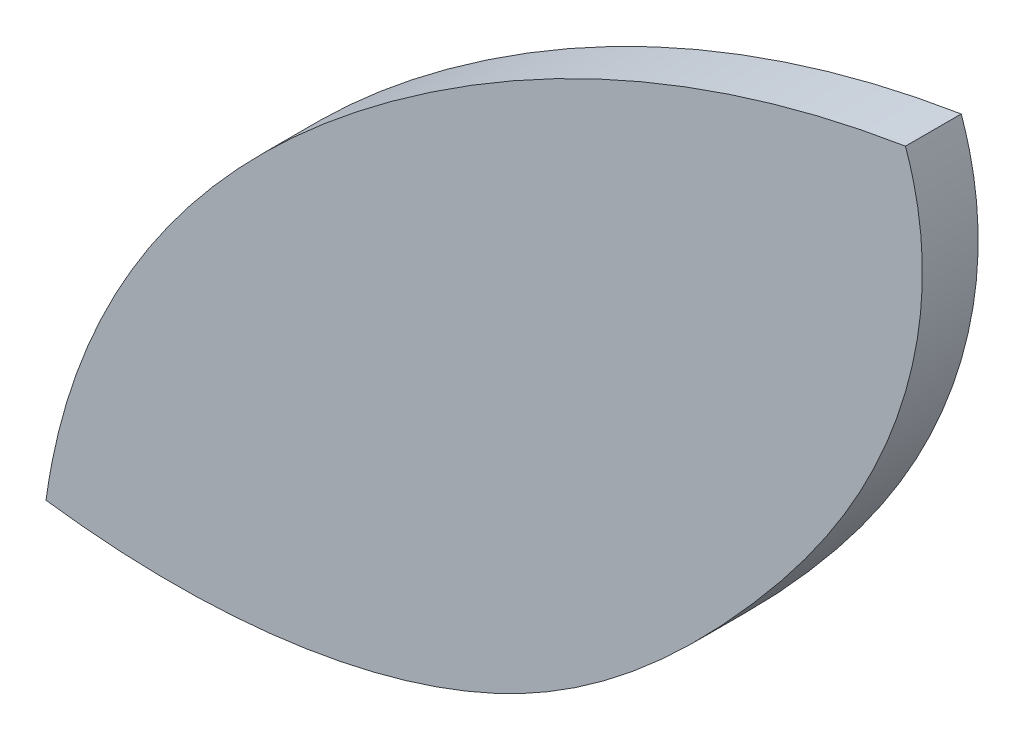
SolidWorks part; units mm, degrees
ref_plane "Piano frontale" through (0, 0, 0) normal (0, 0, 1) x (1, 0, 0)
ref_plane "Piano superiore" through (0, 0, 0) normal (0, 1, 0) x (1, 0, 0)
ref_plane "Piano destro" through (0, 0, 0) normal (1, 0, 0) x (0, 0, -1)
sketch "Schizzo1" plane through (0, 0, 0) normal (0, 0, 1) x (1, 0, 0)
  spline S0 degree 3 poles (0, 0) (1.6435, 12.058) (16.3251, 29.416) (36.5777, 38.0555) (46.2265, 39.6066) knots 0 0 0 0 0.544922 1 1 1 1
  spline S1 degree 3 poles (46.2265, 39.6066) (47.9349, 34.8478) (46.2539, 24.7967) (37.6438, 13.0588) (23.7507, 0.3305) (8.6895, -1.1836) (0, 0) knots 0 0 0 0 0.211914 0.407862 0.616613 1 1 1 1
extrude "Estrusione-Estrusione1" add sketch "Schizzo1" along normal blind 3
